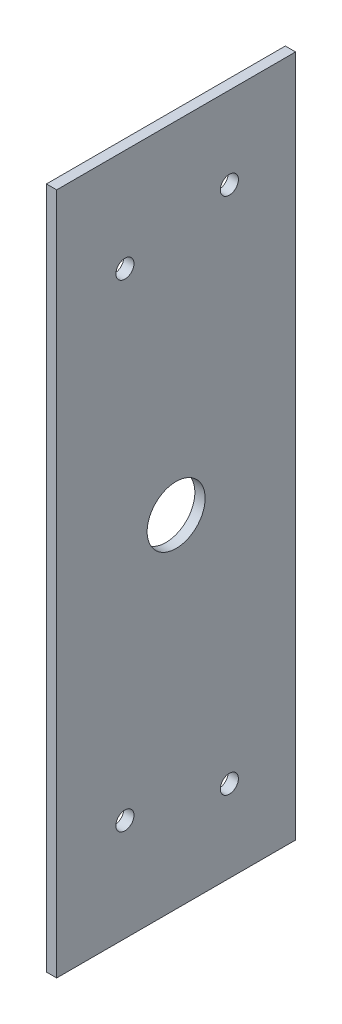
SolidWorks part; units mm, degrees
ref_plane "Front Plane" through (0, 0, 0) normal (1, 0, 0) x (0, 1, 0)
ref_plane "Top Plane" through (0, 0, 0) normal (0, 0, 1) x (0, 1, 0)
ref_plane "Right Plane" through (0, 0, 0) normal (0, 1, 0) x (-1, 0, 0)
sketch "Sketch1" plane through (0, 0, 0) normal (1, 0, 0) x (0, 1, 0)
  line L0 (0, 81.4023) -> (0, 28) construction
  line L1 (-100, 35) -> (100, 35)
  line L2 (-100, 35) -> (-100, -35)
  line L3 (-100, -35) -> (100, -35)
  line L4 (100, 35) -> (100, -35)
  line L13 (-217.085, 0) -> (-8.5, 0) construction
  line L30 (0, 25) -> (0, 8.5) construction
  line L31 (0, -35) -> (0, -114.8153) construction
  line L32 (0, 0) -> (0, -8.5) construction
  line L33 (100, 0) -> (250.2284, 0) construction
  circle A1 centre (-76, -15.6) radius 2.65
  circle A3 centre (76, -15.6) radius 2.65
  circle A4 centre (-70, 15) radius 2.65
  circle A5 centre (70, 15) radius 2.65
  circle A6 centre (0, 0) radius 8.5
  point P4 (0, 35)
  point P6 (-100, 0)
  dimension "D2" = 5.3
  dimension "D13" = 5.3
  dimension "D4" = 17
  dimension "D3" = 20
  dimension "D7" = 76
  dimension "D8" = 15.6
  dimension "D11" = 200
  dimension "D12" = 70
  dimension "D15" = 30
extrude "Boss-Extrude1" add sketch "Sketch1" along normal blind 3
